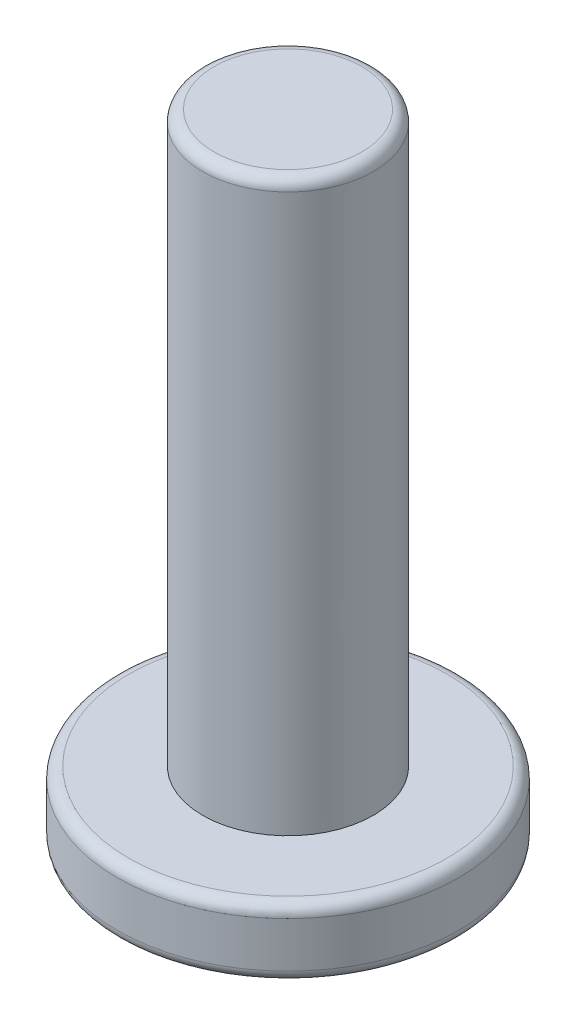
SolidWorks part; units mm, degrees
ref_plane "Front Plane" through (0, 0, 0) normal (0, 0, 1) x (1, 0, 0)
ref_plane "Top Plane" through (0, 0, 0) normal (0, 1, 0) x (1, 0, 0)
ref_plane "Right Plane" through (0, 0, 0) normal (1, 0, 0) x (0, 0, -1)
sketch "Sketch2" plane through (0, 0, 0) normal (0, 0, 1) x (1, 0, 0)
  line L0 (0, 0) -> (3, 0)
  line L1 (3, 0) -> (3, 1.2)
  line L2 (3, 1.2) -> (1.5, 1.2)
  line L3 (1.5, 1.2) -> (1.5, 11.2)
  line L4 (1.5, 11.2) -> (0, 11.2)
  line L5 (0, 11.2) -> (0, 0)
  line L6 (0, 73.1143) -> (0, -37.0787) construction
  dimension "D1" = 3
  dimension "D2" = 10
  dimension "D3" = 1.2
  dimension "D4" = 1.5
revolve "Revolve1" add sketch "Sketch2" angle 360 about L6
fillet "Fillet1" radius 0.2 3 edges at (0, 0, 3) (0, 1.2, 3) (0, 11.2, 1.5)
sketch "Sketch3" plane through (0, 0, 0) normal (0, -1, 0) x (1, 0, 0)
  line L1 (1.4434, 0) -> (0.7217, 1.25)
  line L2 (0.7217, 1.25) -> (-0.7217, 1.25)
  line L3 (-0.7217, 1.25) -> (-1.4434, 0)
  line L4 (-1.4434, 0) -> (-0.7217, -1.25)
  line L5 (-0.7217, -1.25) -> (0.7217, -1.25)
  line L6 (0.7217, -1.25) -> (1.4434, 0)
  circle A0 centre (0, 0) radius 1.25 construction
  dimension "D1" = 2.5
extrude "Cut-Extrude1" cut sketch "Sketch3" against normal blind 1
